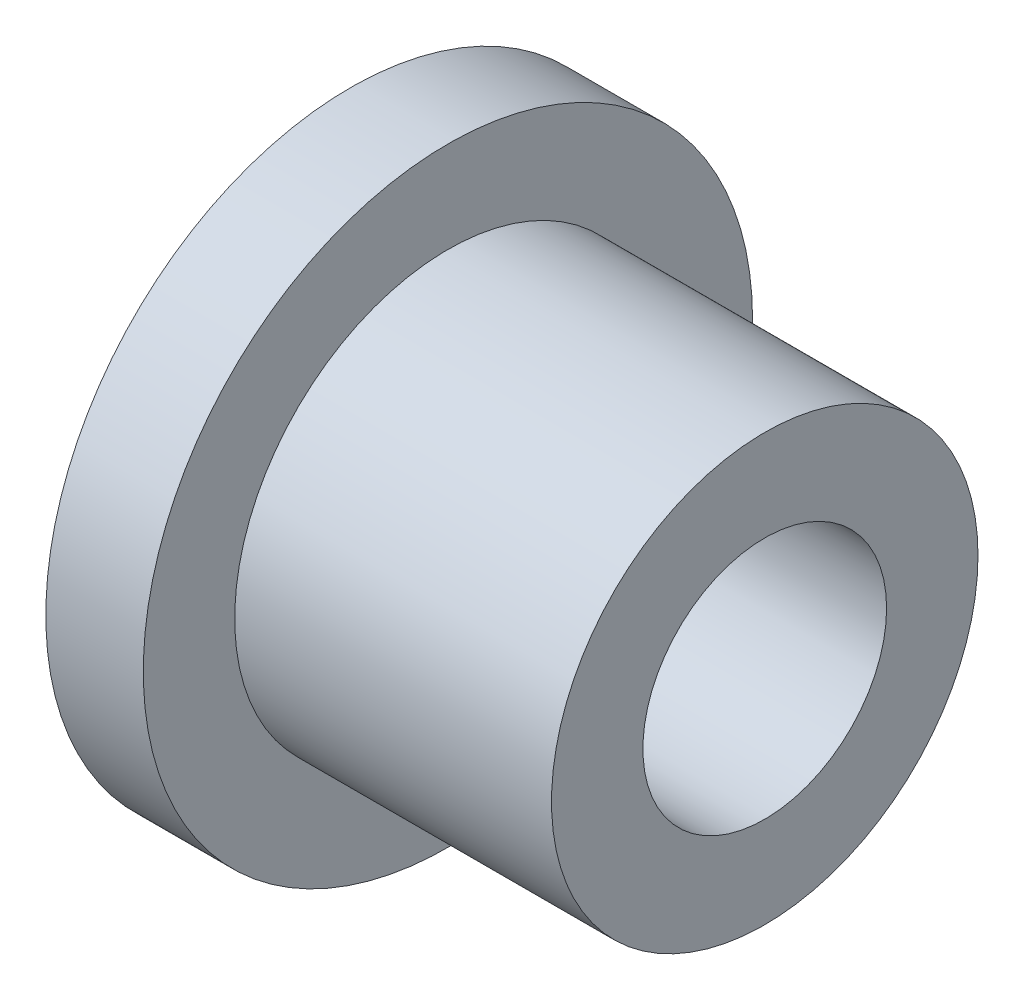
SolidWorks part; units mm, degrees
ref_plane "Front Plane" through (0, 0, 0) normal (0, 0, 1) x (1, 0, 0)
ref_plane "Top Plane" through (0, 0, 0) normal (0, 1, 0) x (1, 0, 0)
ref_plane "Right Plane" through (0, 0, 0) normal (1, 0, 0) x (0, 0, -1)
sketch "Sketch1" plane through (0, 0, 0) normal (0, 0, 1) x (1, 0, 0)
  line L0 (0, 0) -> (-35.5, 0) construction
  line L2 (-24.3, 25) -> (-24.3, 10)
  line L3 (-24.3, 10) -> (9.7, 10)
  line L4 (9.7, 10) -> (9.7, 17.5)
  line L5 (9.7, 17.5) -> (-16.3, 17.5)
  line L6 (-16.3, 17.5) -> (-16.3, 25)
  line L7 (-16.3, 25) -> (-24.3, 25)
  point P4 (0, 0)
  dimension "D1" = 8
  dimension "D2" = 26
  dimension "D3" = 10
  dimension "D4" = 17.5
  dimension "D5" = 25
revolve "Revolve3" add sketch "Sketch1" angle 360 about L0
